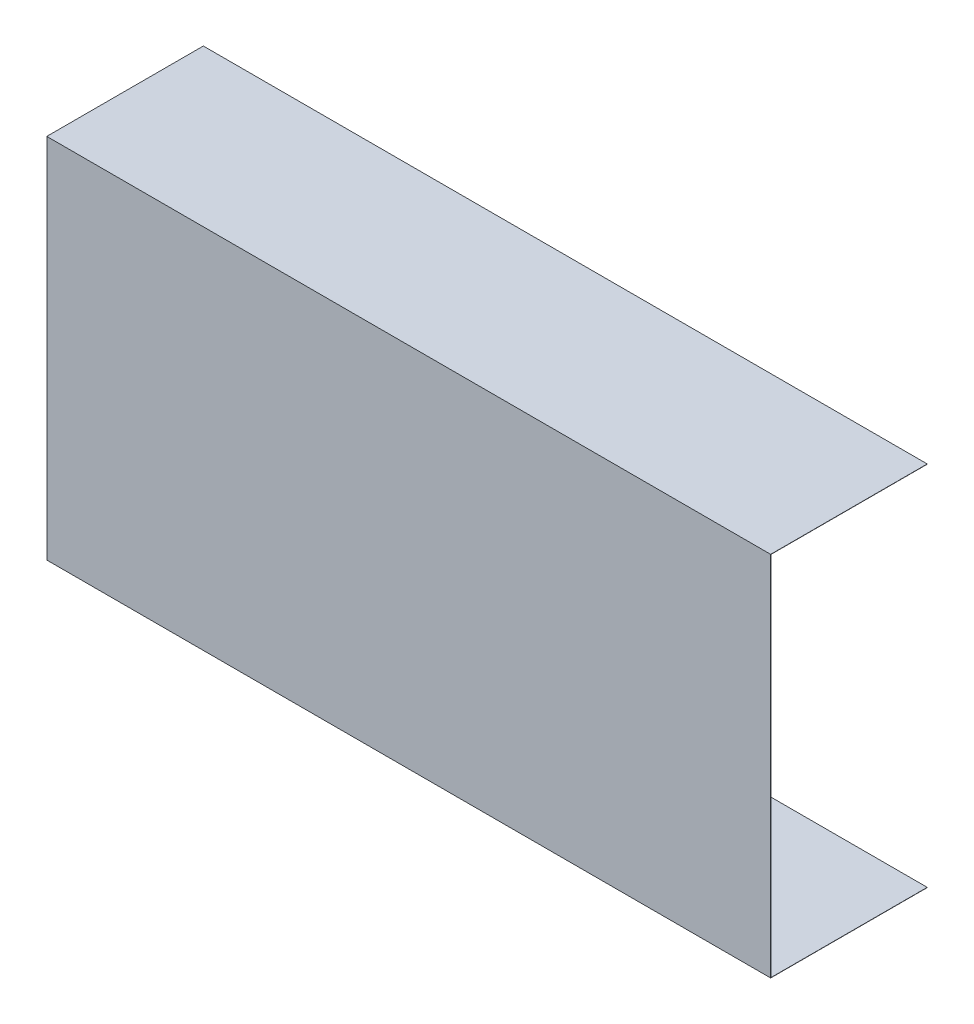
SolidWorks part; units mm, degrees
ref_plane "정면" through (0, 0, 0) normal (0, 0, 1) x (1, 0, 0)
ref_plane "윗면" through (0, 0, 0) normal (0, 1, 0) x (1, 0, 0)
ref_plane "우측면" through (0, 0, 0) normal (1, 0, 0) x (0, 0, -1)
sketch "스케치1" plane through (0, 0, 0) normal (0, 0, 1) x (1, 0, 0)
  line L1 (2761.0036, -285.0894) -> (3056.953, -285.0894)
  line L2 (2761.0036, -285.0894) -> (2761.0036, 173.3902)
  line L3 (2761.0036, 173.3902) -> (3056.953, 173.3902)
  line L4 (3056.953, -285.0894) -> (3056.953, 173.3902)
extrude "보스-돌출1" add sketch "스케치1" along normal blind 64
sketch "스케치2" plane through (3056.953, 0, 0) normal (1, 0, 0) x (0, 0, -1)
  line L0 (0, -285.0894) -> (0, 173.3902) construction
  line L1 (-64, -285.0894) -> (0, -285.0894)
  line L2 (-64, -285.0894) -> (-64, -135.0894)
  line L3 (-64, -135.0894) -> (0, -135.0894)
  line L4 (0, -285.0894) -> (0, -135.0894)
  line M1 (0, -285.0894) -> (0, 173.3902)
  line M2 (0, 173.3902) -> (-64, 173.3902)
  line M3 (-64, 173.3902) -> (-64, -285.0894)
  dimension "D1" = 150
extrude "컷-돌출1" cut sketch "스케치2" against normal blind 1028.33 contours L3 M3 M1 M2
sketch "스케치3" plane through (3056.953, 0, 0) normal (1, 0, 0) x (0, 0, -1)
  line L0 (0, -285.0894) -> (0, -135.0894) construction
  line L1 (0, -284.9894) -> (-63.9, -284.9894)
  line L2 (0, -284.9894) -> (0, -135.1894)
  line L3 (0, -135.1894) -> (-63.9, -135.1894)
  line L4 (-63.9, -284.9894) -> (-63.9, -135.1894)
  line L5 (-64, -285.0894) -> (0, -285.0894) construction
  line L6 (-64, -285.0894) -> (-64, -135.0894) construction
  line L7 (-64, -135.0894) -> (0, -135.0894) construction
  dimension "D1" = 0.1
  dimension "D2" = 0.1
  dimension "D3" = 0.1
extrude "컷-돌출2" cut sketch "스케치3" against normal blind 1028.33
